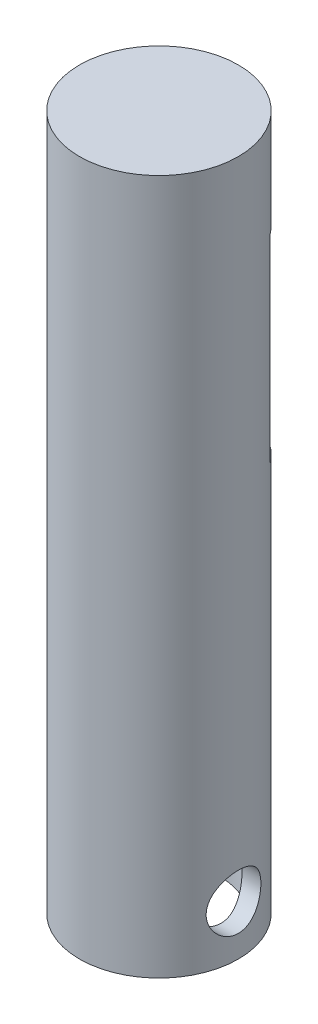
SolidWorks part; units mm, degrees
ref_plane "Front Plane" through (0, 0, 0) normal (0, 0, 1) x (1, 0, 0)
ref_plane "Top Plane" through (0, 0, 0) normal (0, 1, 0) x (1, 0, 0)
ref_plane "Right Plane" through (0, 0, 0) normal (1, 0, 0) x (0, 0, -1)
sketch "Sketch1" plane through (0, 0, 0) normal (0, 1, 0) x (1, 0, 0)
  line L0 (-4.0996, 3) -> (4.0996, 3)
  arc A0 (-4.0996, 3) -> (4.0996, 3) centre (0, 0) ccw
  dimension "D1" = 10.16
  dimension "D2" = 3
extrude "Boss-Extrude1" add sketch "Sketch1" along normal blind 44.45
sketch "Sketch3" plane through (0, 0, 0) normal (0, -1, 0) x (1, 0, 0)
  line L0 (-4.0996, -3) -> (4.0996, -3)
  arc A0 (-4.0996, -3) -> (4.0996, -3) centre (0, 0) ccw
extrude "Boss-Extrude2" add sketch "Sketch3" against normal blind 25.4
sketch "Sketch4" plane through (0, 44.45, 0) normal (0, 1, 0) x (1, 0, 0)
  line L0 (4.0996, 3) -> (-4.0996, 3) construction
  line L1 (-4.0996, 3) -> (4.0996, 3)
  arc A0 (-4.0996, 3) -> (4.0996, 3) centre (0, 0) cw
extrude "Boss-Extrude3" add sketch "Sketch4" against normal blind 6.35
sketch "Sketch5" plane through (0, 0, 0) normal (0, -1, 0) x (1, 0, 0)
  circle A0 centre (0, 0) radius 3.9688
  dimension "D1" = 7.9375
extrude "Cut-Extrude1" cut sketch "Sketch5" against normal blind 6.35
ref_plane "Plane1" through (5.08, 0, 0) normal (1, 0, 0) x (0, 0, -1)
sketch "Sketch6" plane through (5.08, 0, 0) normal (1, 0, 0) x (0, 0, -1)
  circle A0 centre (0, 3.175) radius 1.75
  point P2 (0, 0)
  dimension "D1" = 3.5
  dimension "D2" = 3.175
extrude "Cut-Extrude2" cut sketch "Sketch6" against normal through all
